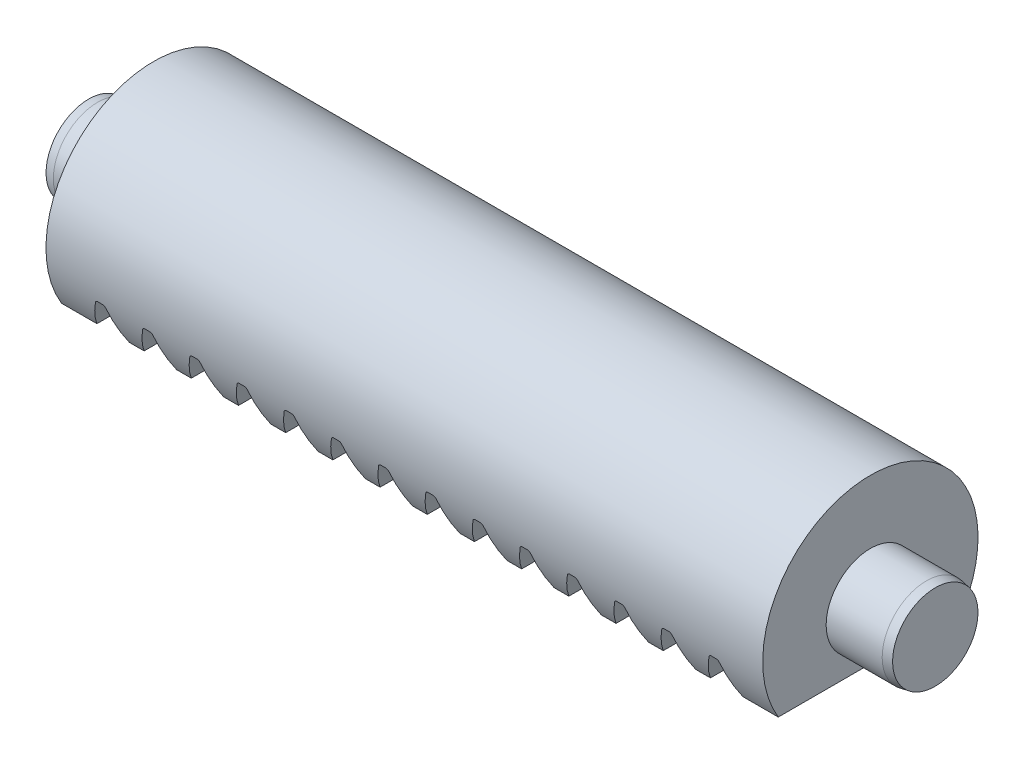
SolidWorks part; units mm, degrees
material "Простая углеродистая сталь"
ref_plane "Спереди" through (0, 0, 0) normal (0, 0, 1) x (1, 0, 0)
ref_plane "Сверху" through (0, 0, 0) normal (0, 1, 0) x (1, 0, 0)
ref_plane "Справа" through (0, 0, 0) normal (1, 0, 0) x (0, 0, -1)
sketch "Эскиз1" plane through (0, 0, 0) normal (0, 0, 1) x (1, 0, 0)
  line L0 (-162.7654, 0) -> (162.7654, 0) construction
  line L1 (-143.5, 0) -> (-143.5, 14.471)
  line L2 (-143.5, 14.471) -> (-140.5, 15)
  line L3 (-140.5, 15) -> (-121.5, 15)
  line L4 (-121.5, 15) -> (-121.5, 36.5)
  line L5 (-121.5, 36.5) -> (121.5, 36.5)
  line L6 (0, 0) -> (0, 90.612) construction
  line L7 (121.5, 15) -> (121.5, 36.5)
  line L8 (140.5, 15) -> (121.5, 15)
  line L9 (143.5, 14.471) -> (140.5, 15)
  line L10 (143.5, 0) -> (143.5, 14.471)
  line L11 (-143.5, 0) -> (143.5, 0)
  point P12 (0, 36.5)
  dimension "D1" = 10
  dimension "D2" = 3
  dimension "D3" = 30
  dimension "D4" = 73
  dimension "D5" = 22
  dimension "D6" = 287
revolve "Повернуть1" add sketch "Эскиз1" angle 360 about L0
sketch "Эскиз2" plane through (0, 0, 0) normal (0, 0, 1) x (1, 0, 0)
  line L0 (121.5, 36.5) -> (-121.5, 36.5) construction
  line L41 (121.5, -36.5) -> (121.5, 36.5) construction
  line L44 (-121.5, -18.9) -> (-121.5, -36.5)
  line L45 (-121.5, -36.5) -> (121.5, -36.5)
  line L46 (121.5, -36.5) -> (121.5, -18.9)
  line L49 (121.5, -18.9) -> (-121.5, -18.9)
  line L50 (-121.5, 36.5) -> (-121.5, -36.5) construction
  point P72 (68.6629, -10.615)
  dimension "D1" = 55.4
extrude "Вырез-Вытянуть1" cut sketch "Эскиз2" against normal through all and the other way through all
sketch "Эскиз3" plane through (0, 0, 0) normal (0, 0, 1) x (1, 0, 0)
  line L0 (109.5, -18.9) -> (105.7358, -8.558)
  line L1 (104.7961, -7.9) -> (103.2039, -7.9)
  line L2 (102.2642, -8.558) -> (98.5, -18.9)
  line L3 (98.5, -18.9) -> (109.5, -18.9)
  line L4 (121.5, -18.9) -> (121.5, 36.5) construction
  line L5 (-121.5, -18.9) -> (121.5, -18.9) construction
  arc A0 (103.2039, -7.9) -> (102.2642, -8.558) centre (103.2039, -8.9) ccw
  arc A1 (105.7358, -8.558) -> (104.7961, -7.9) centre (104.7961, -8.9) ccw
  point P10 (102.5037, -7.9)
  point P13 (105.4963, -7.9)
  dimension "D5" = 1
  dimension "D1" = 11
  dimension "D2" = 40
  dimension "D3" = 11
  dimension "D4" = 12
extrude "Вырез-Вытянуть2" cut sketch "Эскиз3" against normal through all both and the other way through all
pattern_linear "Линейный массив1" count 14 spacing 16 along (-1, 0, 0) of "Вырез-Вытянуть2"
